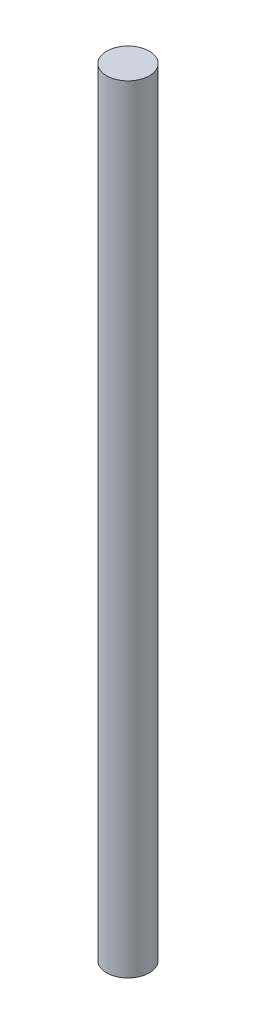
SolidWorks part; units mm, degrees
ref_plane "Front Plane" through (0, 0, 0) normal (0, 0, 1) x (1, 0, 0)
ref_plane "Top Plane" through (0, 0, 0) normal (0, 1, 0) x (1, 0, 0)
ref_plane "Right Plane" through (0, 0, 0) normal (1, 0, 0) x (0, 0, -1)
sketch "Sketch1" plane through (0, 0, 0) normal (0, 1, 0) x (1, 0, 0)
  circle A0 centre (0, 0) radius 11
  dimension "D1" = 22
extrude "Boss-Extrude1" add sketch "Sketch1" along normal blind 400
